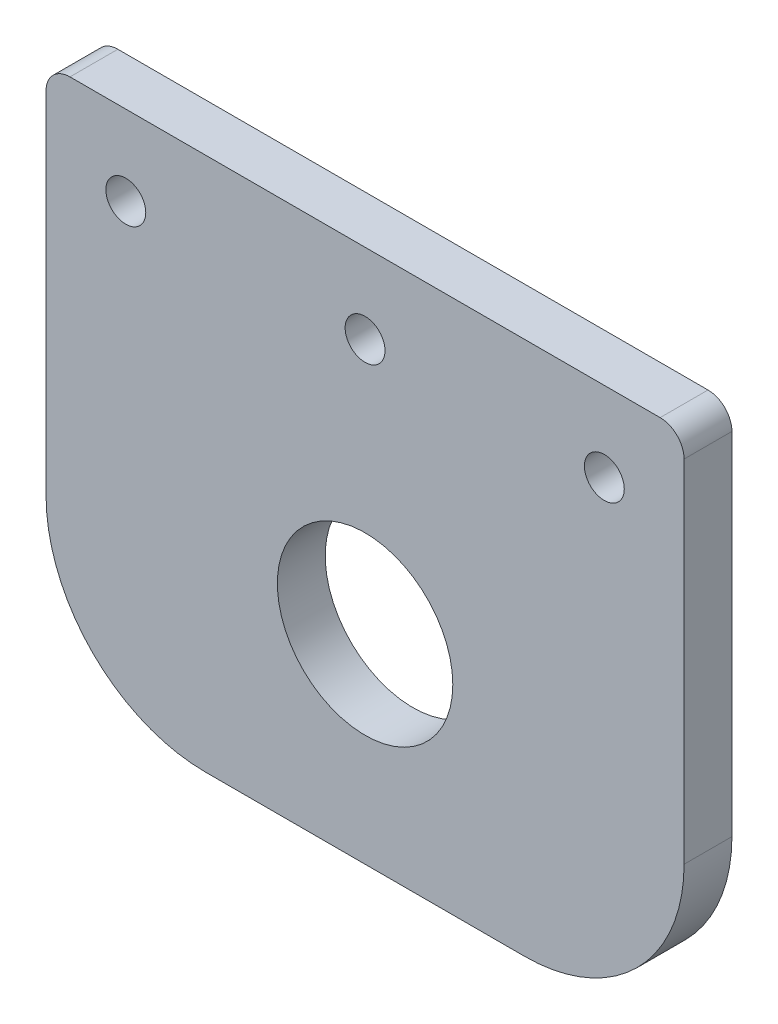
SolidWorks part; units mm, degrees
ref_plane "前视基准面" through (0, 0, 0) normal (0, 0, 1) x (1, 0, 0)
ref_plane "上视基准面" through (0, 0, 0) normal (0, 1, 0) x (1, 0, 0)
ref_plane "右视基准面" through (0, 0, 0) normal (1, 0, 0) x (0, 0, -1)
sketch "草图1" plane through (0, 0, 0) normal (0, 0, 1) x (1, 0, 0)
  line L1 (-40, 33.5) -> (40, 33.5)
  line L2 (-40, 33.5) -> (-40, -33.5)
  line L3 (-40, -33.5) -> (40, -33.5)
  line L4 (40, 33.5) -> (40, -33.5)
  line L5 (-40, 33.5) -> (40, -33.5) construction
  line L6 (-40, -33.5) -> (40, 33.5) construction
  circle A0 centre (0, -8.5) radius 11
  point P0 (0, 0)
  dimension "D1" = 22
  dimension "D2" = 25
  dimension "D3" = 80
  dimension "D4" = 42
extrude "凸台-拉伸1" add sketch "草图1" along normal blind 6
sketch "草图2" plane through (0, 0, 0) normal (0, 0, -1) x (-1, 0, 0)
  line L0 (-64.1083, 23.5) -> (65.158, 23.5) construction
  line L1 (-40, 33.5) -> (40, 33.5) construction
  line L2 (0, 56.7602) -> (0, -32.4666) construction
  circle A0 centre (-30, 23.5) radius 2.5
  circle A1 centre (30, 23.5) radius 2.5
  circle A2 centre (0, 23.5) radius 2.5
  dimension "D2" = 5
  dimension "D4" = 5
  dimension "D1" = 10
  dimension "D3" = 30
extrude "切除-拉伸1" cut sketch "草图2" against normal blind 10
fillet "圆角1" radius 20 2 edges at (40, -33.5, 3) (-40, -33.5, 3)
fillet "圆角2" radius 3 2 edges at (-40, 33.5, 3) (40, 33.5, 3)
